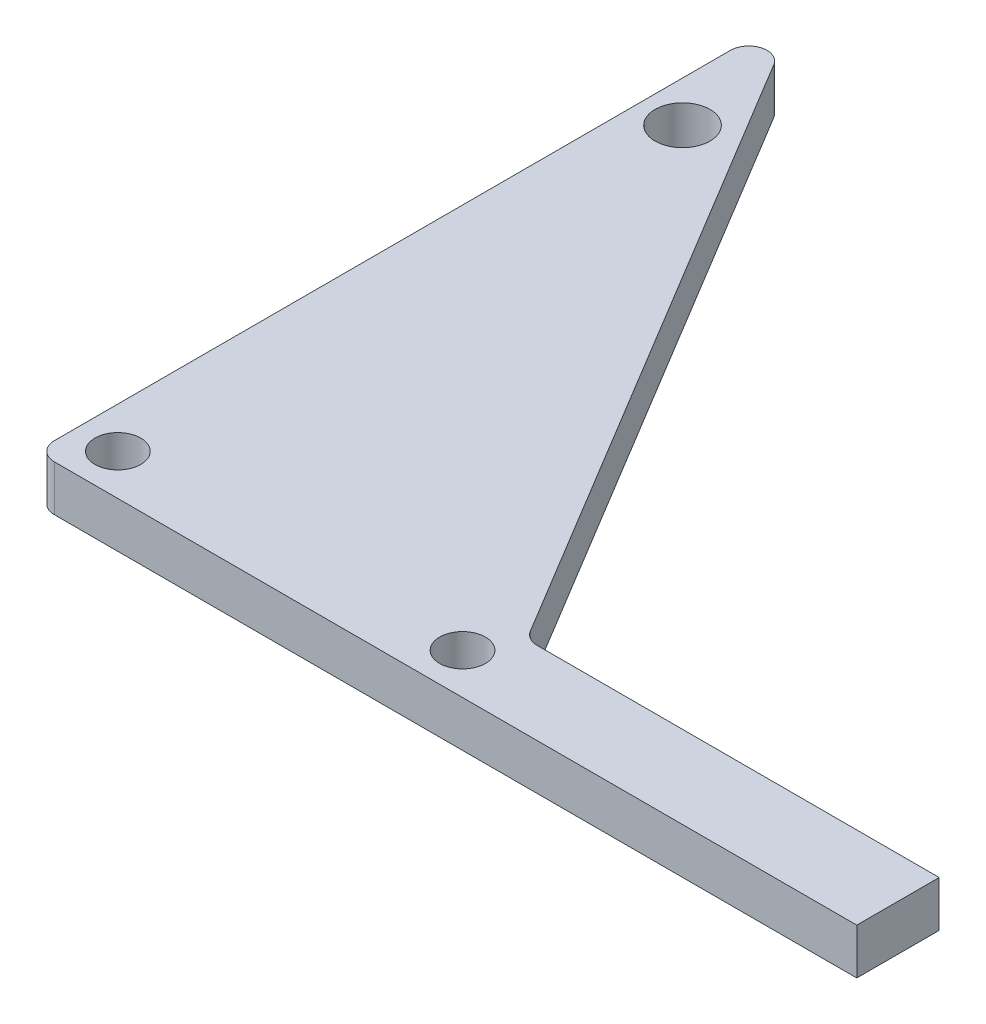
SolidWorks part; units mm, degrees
ref_plane "Front Plane" through (0, 0, 0) normal (0, 0, 1) x (1, 0, 0)
ref_plane "Top Plane" through (0, 0, 0) normal (0, 1, 0) x (1, 0, 0)
ref_plane "Right Plane" through (0, 0, 0) normal (1, 0, 0) x (0, 0, -1)
sketch "Sketch1" plane through (0, 0, 0) normal (0, 1, 0) x (1, 0, 0)
  line L0 (0, 0) -> (0, 105.41)
  line L1 (0, 105.41) -> (63.5, 0)
  line L2 (63.5, 0) -> (0, 0)
  dimension "D1" = 105.41
  dimension "D2" = 63.5
extrude "Boss-Extrude1" add sketch "Sketch1" along normal blind 6.35
fillet "Fillet1" radius 2.54 2 edges at (0, 3.175, 0) (0, 3.175, -105.41)
sketch "Sketch3" plane through (0, 6.35, 0) normal (0, 1, 0) x (1, 0, 0)
  line L1 (1.8598, 98.7185) -> (27.3724, 0) construction
  line L2 (2.54, 0) -> (63.5, 0) construction
  line L3 (0.7439, 0.7439) -> (39.6278, 39.6278) construction
  line L4 (63.5, 0) -> (4.7157, 97.5819) construction
  line L6 (63.5, 0) -> (0, 35.8825) construction
  line L9 (0, 96.2712) -> (0, 2.54) construction
  circle A0 centre (5.673, 83.9637) radius 3.81
  circle A1 centre (5.673, 5.673) radius 3.175
  arc A2 (4.7157, 97.5819) -> (0, 96.2712) centre (2.54, 96.2712) ccw construction
  arc A3 (0, 2.54) -> (2.54, 0) centre (2.54, 2.54) ccw construction
  circle A6 centre (53.4607, 5.673) radius 3.175
  dimension "D1" = 7.62
  dimension "D2" = 6.35
  dimension "D4" = 29.465
  dimension "D7" = 6.35
  dimension "D3" = 12.7
  dimension "D5" = 2.413
  dimension "D6" = 46.2628
extrude "Cut-Extrude1" cut sketch "Sketch3" against normal through all
ref_plane "Plane1" through (57.15, 0, 0) normal (1, 0, 0) x (0, 0, -1)
sketch "Sketch7" plane through (57.15, 0, 0) normal (1, 0, 0) x (0, 0, -1)
  line L0 (0, 0) -> (97.5819, 0) construction
  line L1 (0, 6.35) -> (11.43, 6.35)
  line L2 (0, 6.35) -> (0, 0)
  line L3 (0, 0) -> (11.43, 0)
  line L4 (11.43, 6.35) -> (11.43, 0)
  dimension "D1" = 11.43
extrude "Boss-Extrude3" add sketch "Sketch7" along normal blind 56.642
sketch "Sketch8" plane through (57.15, 0, 0) normal (1, 0, 0) x (0, 0, -1)
  line L1 (11.43, 0) -> (10.541, 0)
  line L2 (11.43, 0) -> (11.43, 6.35)
  line L3 (11.43, 6.35) -> (10.541, 6.35)
  line L4 (10.541, 0) -> (10.541, 6.35)
extrude "Boss-Extrude4" add sketch "Sketch8" against normal blind 1.27
fillet "Fillet2" radius 2.54 1 edges at (56.6145, 3.175, -11.43)
